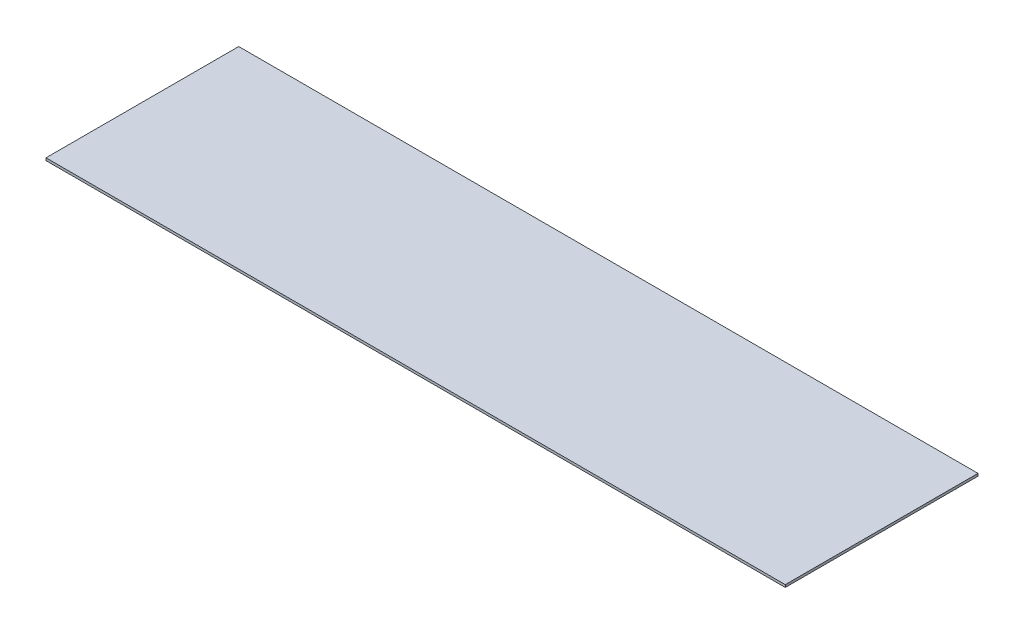
SolidWorks part; units mm, degrees
ref_plane "Front Plane" through (0, 0, 0) normal (0, 0, 1) x (1, 0, 0)
ref_plane "Top Plane" through (0, 0, 0) normal (0, 1, 0) x (1, 0, 0)
ref_plane "Right Plane" through (0, 0, 0) normal (1, 0, 0) x (0, 0, -1)
sketch "Sketch1" plane through (0, 0, 0) normal (0, 1, 0) x (1, 0, 0)
  line L1 (-237.744, -61.976) -> (237.744, -61.976)
  line L2 (-237.744, -61.976) -> (-237.744, 61.976)
  line L3 (-237.744, 61.976) -> (237.744, 61.976)
  line L4 (237.744, -61.976) -> (237.744, 61.976)
  line L5 (-237.744, -61.976) -> (237.744, 61.976) construction
  line L6 (-237.744, 61.976) -> (237.744, -61.976) construction
  point P0 (0, 0)
  dimension "D1" = 475.488
  dimension "D2" = 123.952
extrude "Boss-Extrude1" add sketch "Sketch1" along normal blind 1.5875
